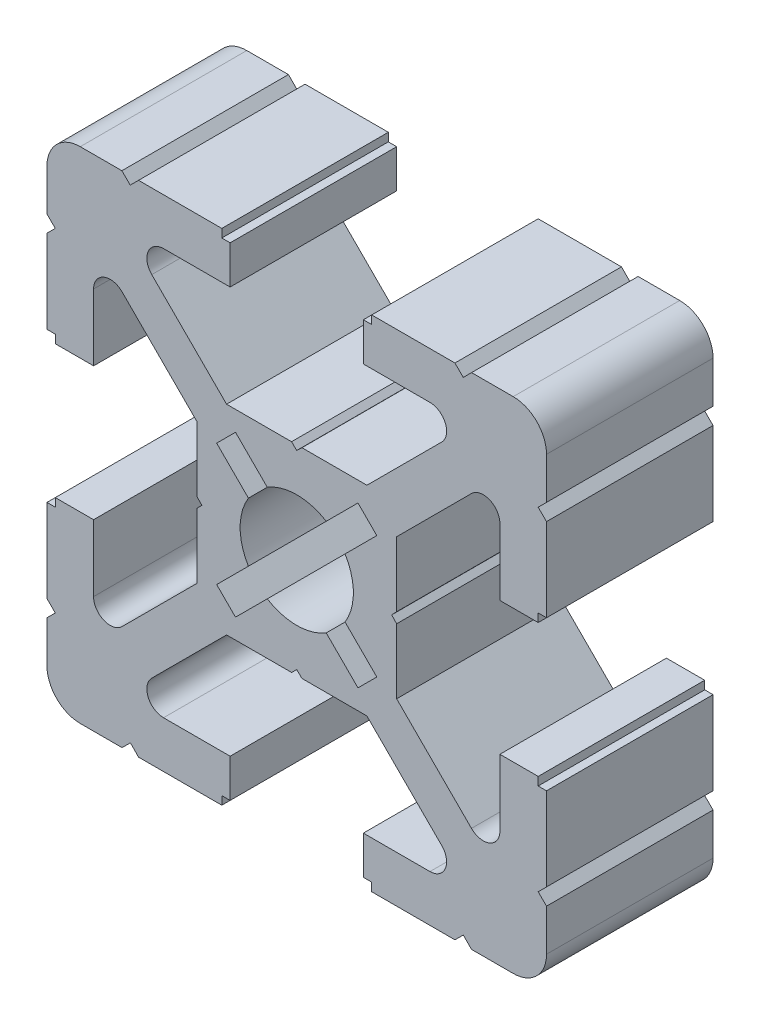
SolidWorks part; units mm, degrees
material "1060 Alloy"
ref_plane "Front" through (0, 0, 0) normal (0, 0, 1) x (1, 0, 0)
ref_plane "Top" through (0, 0, 0) normal (0, 1, 0) x (1, 0, 0)
ref_plane "Right" through (0, 0, 0) normal (1, 0, 0) x (0, 0, -1)
sketch "Sketch1" plane through (0, 0, 0) normal (0, 0, 1) x (1, 0, 0)
  line L0 (-2.9023, 1.771) -> (-4.8083, 3.677)
  line L1 (-4.8083, 3.677) -> (-3.677, 4.8083)
  line L2 (-3.677, 4.8083) -> (-1.771, 2.9023)
  line L3 (1.771, 2.9023) -> (3.677, 4.8083)
  line L4 (3.677, 4.8083) -> (4.8083, 3.677)
  line L5 (4.8083, 3.677) -> (2.9023, 1.771)
  line L6 (2.9023, -1.771) -> (4.8083, -3.677)
  line L7 (4.8083, -3.677) -> (3.677, -4.8083)
  line L8 (3.677, -4.8083) -> (1.771, -2.9023)
  line L9 (-1.771, -2.9023) -> (-3.677, -4.8083)
  line L10 (-3.677, -4.8083) -> (-4.8083, -3.677)
  line L11 (-4.8083, -3.677) -> (-2.9023, -1.771)
  line L12 (13, 15) -> (10.5, 15)
  line L13 (10.5, 15) -> (10, 14.5)
  line L14 (10, 14.5) -> (9.5, 15)
  line L15 (9.5, 15) -> (4.5, 15)
  line L16 (4.5, 15) -> (4.5, 14.5)
  line L17 (4.5, 14.5) -> (4, 14.5)
  line L18 (4, 14.5) -> (4, 12.2)
  line L19 (4, 12.2) -> (8, 12.2)
  line L20 (8.7071, 10.4929) -> (4.2142, 6)
  line L21 (4.2142, 6) -> (0.3125, 6)
  line L22 (0.3125, 6) -> (0, 5.7)
  line L23 (0, 5.7) -> (-0.3125, 6)
  line L24 (-0.3125, 6) -> (-4.2142, 6)
  line L25 (-4.2142, 6) -> (-8.7071, 10.4929)
  line L26 (-8, 12.2) -> (-4, 12.2)
  line L27 (-4, 12.2) -> (-4, 14.5)
  line L28 (-4, 14.5) -> (-4.5, 14.5)
  line L29 (-4.5, 14.5) -> (-4.5, 15)
  line L30 (-4.5, 15) -> (-9.5, 15)
  line L31 (-9.5, 15) -> (-10, 14.5)
  line L32 (-10, 14.5) -> (-10.5, 15)
  line L33 (-10.5, 15) -> (-13, 15)
  line L34 (-15, 13) -> (-15, 10.5)
  line L35 (-15, 10.5) -> (-14.5, 10)
  line L36 (-14.5, 10) -> (-15, 9.5)
  line L37 (-15, 9.5) -> (-15, 4.5)
  line L38 (-15, 4.5) -> (-14.5, 4.5)
  line L39 (-14.5, 4.5) -> (-14.5, 4)
  line L40 (-14.5, 4) -> (-12.2, 4)
  line L41 (-12.2, 4) -> (-12.2, 8)
  line L42 (-10.4929, 8.7071) -> (-6, 4.2142)
  line L43 (-6, 4.2142) -> (-6, 0.3125)
  line L44 (-6, 0.3125) -> (-5.7, 0)
  line L45 (-5.7, 0) -> (-6, -0.3125)
  line L46 (-6, -0.3125) -> (-6, -4.2142)
  line L47 (-6, -4.2142) -> (-10.4929, -8.7071)
  line L48 (-12.2, -8) -> (-12.2, -4)
  line L49 (-12.2, -4) -> (-14.5, -4)
  line L50 (-14.5, -4) -> (-14.5, -4.5)
  line L51 (-14.5, -4.5) -> (-15, -4.5)
  line L52 (-15, -4.5) -> (-15, -9.5)
  line L53 (-15, -9.5) -> (-14.5, -10)
  line L54 (-14.5, -10) -> (-15, -10.5)
  line L55 (-15, -10.5) -> (-15, -13)
  line L56 (-13, -15) -> (-10.4899, -15)
  line L57 (-10.4899, -15) -> (-9.9899, -14.5)
  line L58 (-9.9899, -14.5) -> (-9.5, -15)
  line L59 (-9.5, -15) -> (-4.5, -15)
  line L60 (-4.5, -15) -> (-4.5, -14.5)
  line L61 (-4.5, -14.5) -> (-4, -14.5)
  line L62 (-4, -14.5) -> (-4, -12.2)
  line L63 (-4, -12.2) -> (-8, -12.2)
  line L64 (-8.7071, -10.4929) -> (-4.2142, -6)
  line L65 (-4.2142, -6) -> (-0.3125, -6)
  line L66 (-0.3125, -6) -> (0, -5.7)
  line L67 (0, -5.7) -> (0.3125, -6)
  line L68 (0.3125, -6) -> (4.2142, -6)
  line L69 (4.2142, -6) -> (8.7071, -10.4929)
  line L70 (8, -12.2) -> (4, -12.2)
  line L71 (4, -12.2) -> (4, -14.5)
  line L72 (4, -14.5) -> (4.5, -14.5)
  line L73 (4.5, -14.5) -> (4.5, -15)
  line L74 (4.5, -15) -> (9.5, -15)
  line L75 (9.5, -15) -> (10, -14.5)
  line L76 (10, -14.5) -> (10.5, -15)
  line L77 (10.5, -15) -> (13, -15)
  line L78 (15, -13) -> (15, -10.5)
  line L79 (15, -10.5) -> (14.5, -10)
  line L80 (14.5, -10) -> (15, -9.5)
  line L81 (15, -9.5) -> (15, -4.5)
  line L82 (15, -4.5) -> (14.5, -4.5)
  line L83 (14.5, -4.5) -> (14.5, -4)
  line L84 (14.5, -4) -> (12.2, -4)
  line L85 (12.2, -4) -> (12.2, -8)
  line L86 (10.4929, -8.7071) -> (6, -4.2142)
  line L87 (6, -4.2142) -> (6, -0.3125)
  line L88 (6, -0.3125) -> (5.7, 0)
  line L89 (5.7, 0) -> (6, 0.3125)
  line L90 (6, 0.3125) -> (6, 4.2142)
  line L91 (6, 4.2142) -> (10.4929, 8.7071)
  line L92 (12.2, 8) -> (12.2, 4)
  line L93 (12.2, 4) -> (14.5, 4)
  line L94 (14.5, 4) -> (14.5, 4.5)
  line L95 (14.5, 4.5) -> (15, 4.5)
  line L96 (15, 4.5) -> (15, 9.5)
  line L97 (15, 9.5) -> (14.5, 10)
  line L98 (14.5, 10) -> (15, 10.5)
  line L99 (15, 10.5) -> (15, 13)
  arc A0 (-1.771, 2.9023) -> (1.771, 2.9023) centre (0, 0) cw
  arc A1 (2.9023, 1.771) -> (2.9023, -1.771) centre (0, 0) cw
  arc A2 (1.771, -2.9023) -> (-1.771, -2.9023) centre (0, 0) cw
  arc A3 (-2.9023, -1.771) -> (-2.9023, 1.771) centre (0, 0) cw
  arc A4 (8, 12.2) -> (8.7071, 10.4929) centre (8, 11.2) cw
  arc A5 (-8.7071, 10.4929) -> (-8, 12.2) centre (-8, 11.2) cw
  arc A6 (-13, 15) -> (-15, 13) centre (-13, 13) ccw
  arc A7 (-12.2, 8) -> (-10.4929, 8.7071) centre (-11.2, 8) cw
  arc A8 (-10.4929, -8.7071) -> (-12.2, -8) centre (-11.2, -8) cw
  arc A9 (-15, -13) -> (-13, -15) centre (-13, -13) ccw
  arc A10 (-8, -12.2) -> (-8.7071, -10.4929) centre (-8, -11.2) cw
  arc A11 (8.7071, -10.4929) -> (8, -12.2) centre (8, -11.2) cw
  arc A12 (13, -15) -> (15, -13) centre (13, -13) ccw
  arc A13 (12.2, -8) -> (10.4929, -8.7071) centre (11.2, -8) cw
  arc A14 (10.4929, 8.7071) -> (12.2, 8) centre (11.2, 8) cw
  arc A15 (15, 13) -> (13, 15) centre (13, 13) ccw
  dimension "D3" = 3.4
  dimension "D7" = 2
  dimension "D1" = 30
  dimension "D2" = 30
  dimension "D4" = 9
  dimension "D5" = 9
  dimension "D6" = 8
  dimension "D8" = 2.8
extrude "Boss-Extrude1" add sketch "Sketch1" along normal blind 10
